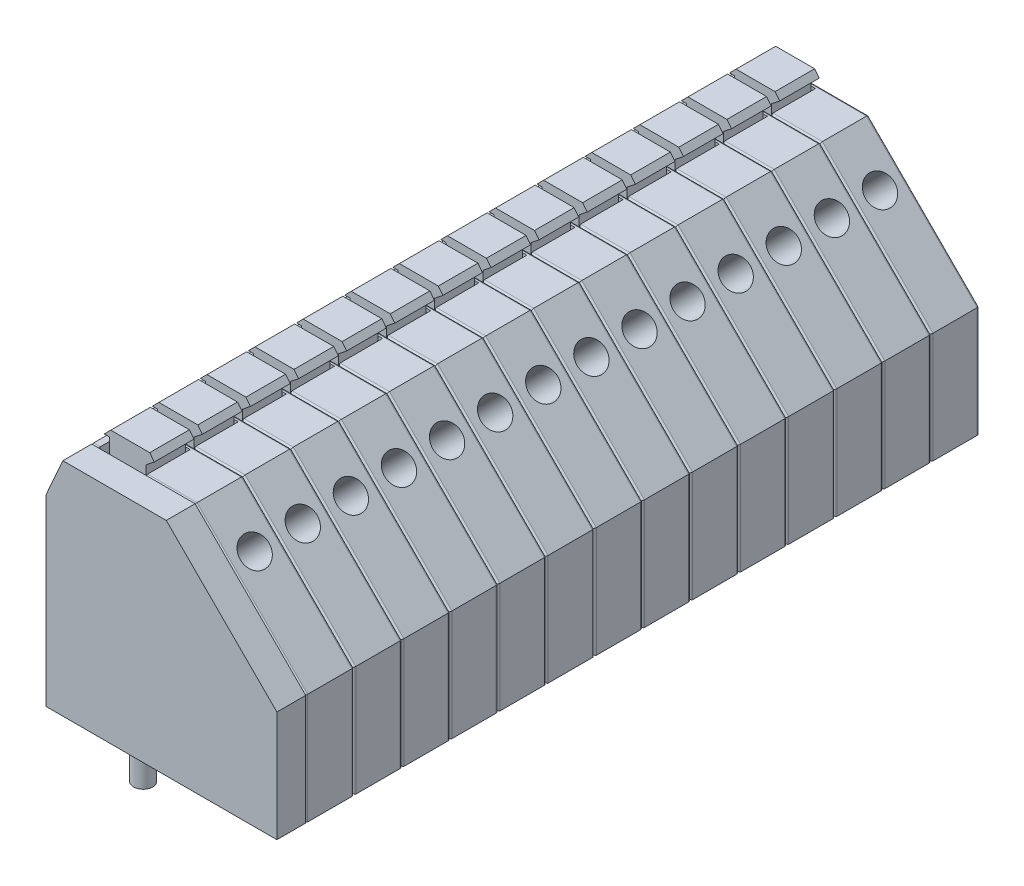
SolidWorks part; units mm, degrees
ref_plane "Front Plane" through (0, 0, 0) normal (0, 0, 1) x (1, 0, 0)
ref_plane "Top Plane" through (0, 0, 0) normal (0, 1, 0) x (1, 0, 0)
ref_plane "Right Plane" through (0, 0, 0) normal (1, 0, 0) x (0, 0, -1)
sketch "Sketch1" plane through (0, 0, 0) normal (0, 0, 1) x (1, 0, 0)
  line L0 (0, 0) -> (12, 0)
  line L1 (12, 0) -> (12, 5.75)
  line L2 (12, 5.75) -> (6.25, 11.5)
  line L3 (6.25, 11.5) -> (0.8751, 11.5)
  line L5 (0.8751, 11.5) -> (0, 9.5271)
  line L6 (0, 9.5271) -> (0, 0)
  dimension "D1" = 12
  dimension "D2" = 11.5
  dimension "D3" = 135
  dimension "D4" = 5.75
extrude "Boss-Extrude1" add sketch "Sketch1" along normal blind 2.5 contours L2 L3 L5 L6 L0 L1
sketch "Sketch2" plane through (8.875, 8.875, 0) normal (0.7071, 0.7071, 0) x (0, 0, -1)
  line L0 (-1.25, 3.7123) -> (-1.25, 1.1012) construction
  line L1 (-2.5, 3.7123) -> (0, 3.7123) construction
  circle A0 centre (-1.25, 1.1012) radius 0.75
  dimension "D1" = 1.5
extrude "Cut-Extrude1" cut sketch "Sketch2" against normal blind 5
sketch "Sketch3" plane through (0, 11.5, 0) normal (0, 1, 0) x (1, 0, 0)
  line L1 (1.2198, -0.1897) -> (3.6834, -0.1897)
  line L2 (1.2198, -0.1897) -> (1.2198, -3.3275)
  line L3 (1.2198, -3.3275) -> (3.6834, -3.3275)
  line L4 (3.6834, -0.1897) -> (3.6834, -3.3275)
extrude "Cut-Extrude2" cut sketch "Sketch3" against normal blind 2
sketch "Sketch9" plane through (0, 0, 0) normal (0, 0, -1) x (-1, 0, 0)
  circle A0 centre (-7.8248, 2.6388) radius 0.7557
  circle A1 centre (-2.3626, 8.1308) radius 0.7557
extrude "Cut-Extrude3" cut sketch "Sketch9" against normal blind 0.2
sketch "Sketch10" plane through (0, 0, 0.1897) normal (0, 0, 1) x (1, 0, 0)
  line L0 (1.5401, 9.5) -> (1.5401, 12.0288)
  line L1 (3.6834, 9.5) -> (1.2198, 9.5) construction
  line L2 (1.5401, 12.0288) -> (1.2746, 12.0288)
  line L3 (1.2746, 12.0288) -> (1.6161, 12.3703)
  line L4 (1.6161, 12.3703) -> (3.641, 12.3703)
  line L5 (3.641, 12.3703) -> (3.8807, 12.0692)
  line L6 (3.8807, 12.0692) -> (3.4526, 11.7283)
  line L7 (3.4526, 11.7283) -> (3.4526, 9.5)
  line L8 (3.6834, 9.5) -> (1.2198, 9.5) construction
  line L9 (3.4526, 9.5) -> (1.5401, 9.5)
extrude "Boss-Extrude2" add sketch "Sketch10" along normal offset from surface (2.0603 mm away) 0.25 up to face at (4.0932, 8.0277, 2.5)
fillet "Fillet1" radius 0.1 18 edges at (9.125, 8.625, 0) (3.5626, 11.5, 0) (0.4376, 10.5135, 0) (0, 4.7635, 0) (6, 0, 0) (12, 2.875, 0) (1.6069, 8.1308, 0) (7.0691, 2.6388, 0) (2.4516, 9.5, 2.5) (3.6834, 10.5, 2.5) (4.9667, 11.5, 2.5) (9.125, 8.625, 2.5) (12, 2.875, 2.5) (6, 0, 2.5) (0, 4.7635, 2.5) (0.4376, 10.5135, 2.5) (1.0475, 11.5, 2.5) (1.2198, 10.5, 2.5)
pattern_linear "LPattern1" count 14 spacing 2.5 along (0, 0, 1) of bodies 112
sketch "Sketch11" plane through (0, 0, 0) normal (0, -1, 0) x (1, 0, 0)
  line L0 (0, 3.75) -> (5.3604, 3.75) construction
  line L1 (0, 4.9) -> (0, 2.6) construction
  line L2 (12, 1.25) -> (10.6681, 1.25) construction
  line L3 (12, 2.4) -> (12, 0.1) construction
  circle A0 centre (7.3, 1.25) radius 0.5
  circle A1 centre (2.3, 3.75) radius 0.5
  point P8 (0, 0)
  dimension "D1" = 1
  dimension "D2" = 2.3
  dimension "D3" = 5
extrude "Boss-Extrude3" add sketch "Sketch11" along normal blind 3.6
pattern_linear "LPattern2" count 7 spacing 5 along (0, 0, 1) of "Boss-Extrude3"
sketch "Sketch12" plane through (0, 0, 35) normal (0, 0, 1) x (1, 0, 0)
  line L0 (0, 0) -> (0, 9.5271)
  line L1 (0, 9.5271) -> (0.8751, 11.5)
  line L2 (0.8751, 11.5) -> (6.25, 11.5)
  line L3 (6.25, 11.5) -> (12, 5.75)
  line L4 (12, 5.75) -> (12, 0)
  line L5 (12, 0) -> (0, 0)
extrude "Boss-Extrude4" add sketch "Sketch12" along normal blind 1.5
ref_point "Point2"
